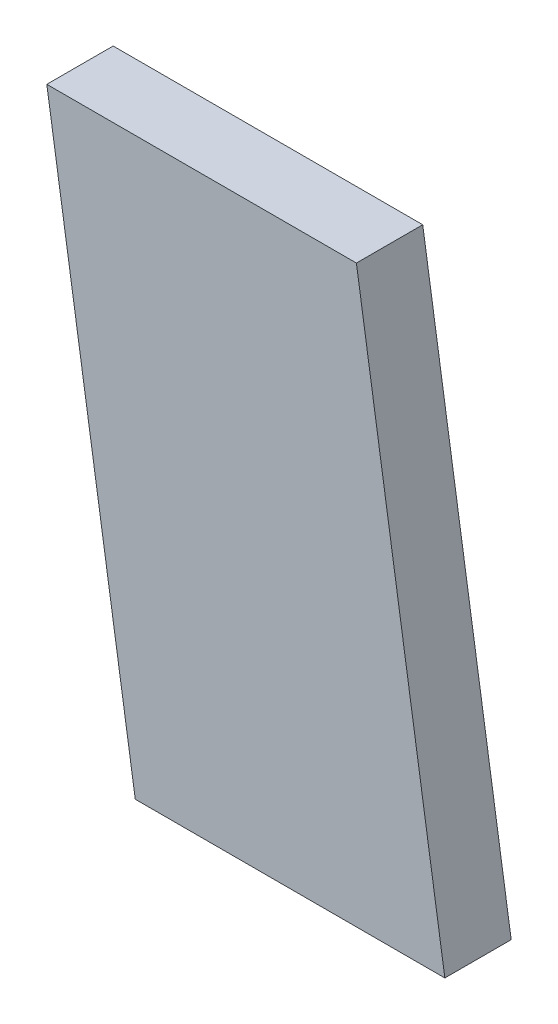
SolidWorks part; units mm, degrees
ref_plane "Front Plane" through (0, 0, 0) normal (0, 0, 1) x (1, 0, 0)
ref_plane "Top Plane" through (0, 0, 0) normal (0, 1, 0) x (1, 0, 0)
ref_plane "Right Plane" through (0, 0, 0) normal (1, 0, 0) x (0, 0, -1)
sketch "Sketch1" plane through (0, 0, 0) normal (0, 0, 1) x (1, 0, 0)
  line L0 (2000, 450) -> (1980, 580)
  line L1 (1980, 580) -> (2050, 580)
  line L2 (2050, 580) -> (2070, 450)
  line L3 (2070, 450) -> (2000, 450)
extrude "Boss-Extrude1" add sketch "Sketch1" along normal blind 15
